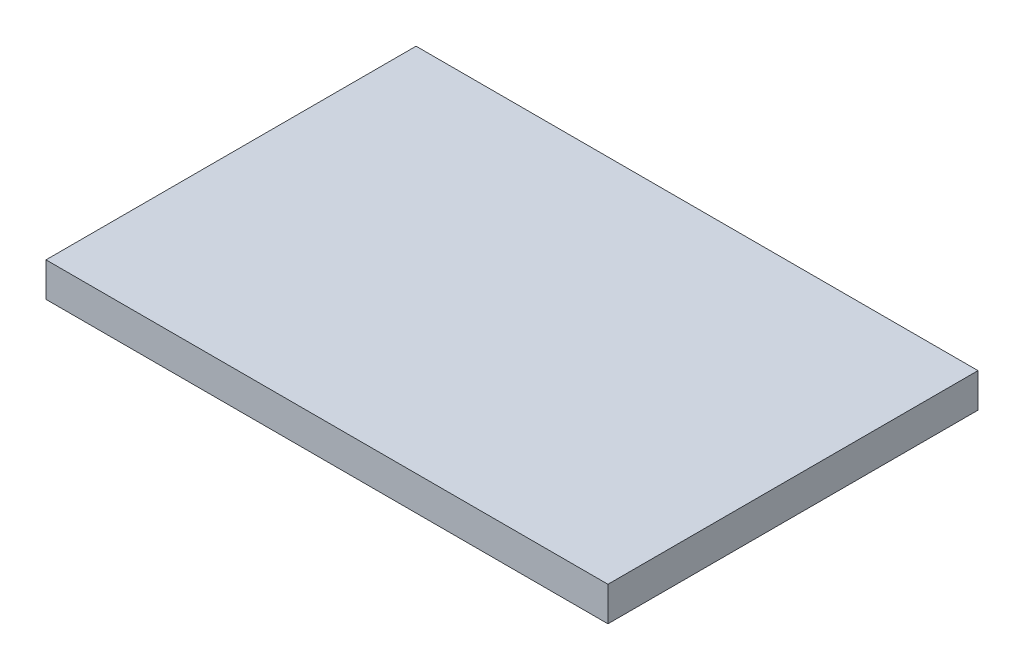
SolidWorks part; units mm, degrees
ref_plane "Front Plane" through (0, 0, 0) normal (0, 0, 1) x (1, 0, 0)
ref_plane "Top Plane" through (0, 0, 0) normal (0, 1, 0) x (1, 0, 0)
ref_plane "Right Plane" through (0, 0, 0) normal (1, 0, 0) x (0, 0, -1)
sketch "Sketch3" plane through (0, 0, 0) normal (0, 1, 0) x (1, 0, 0)
  line L1 (0, 0) -> (164, 0)
  line L2 (0, 0) -> (0, 108)
  line L3 (0, 108) -> (164, 108)
  line L4 (164, 0) -> (164, 108)
  dimension "D1" = 108
  dimension "D2" = 164
extrude "Boss-Extrude1" add sketch "Sketch3" along normal blind 10
